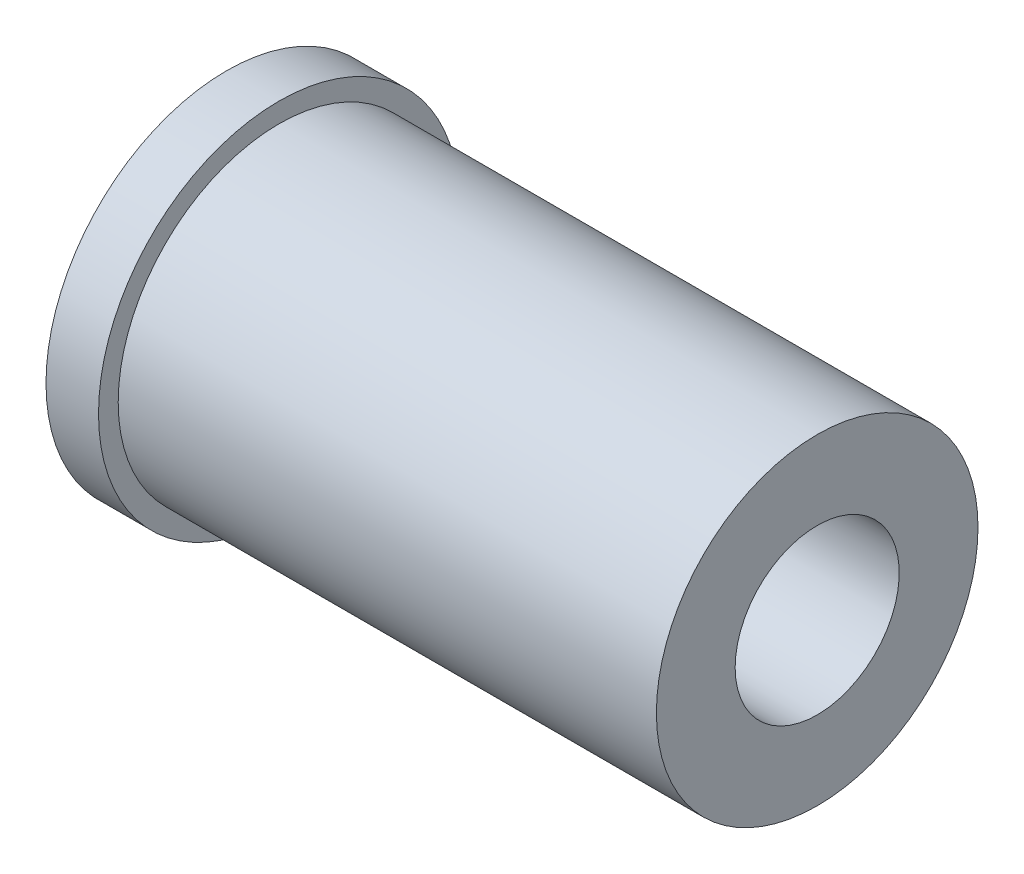
SolidWorks part; units mm, degrees
material "AISI 304"
ref_plane "前视基准面" through (0, 0, 0) normal (0, 0, 1) x (1, 0, 0)
ref_plane "上视基准面" through (0, 0, 0) normal (0, 1, 0) x (1, 0, 0)
ref_plane "右视基准面" through (0, 0, 0) normal (1, 0, 0) x (0, 0, -1)
sketch "草图1" plane through (0, 0, 0) normal (0, 0, 1) x (1, 0, 0)
  line L0 (0, 0) -> (7, 0) construction
  line L1 (0, 1.5) -> (0, 2.75)
  line L2 (0, 2.75) -> (0.8, 2.75)
  line L3 (0.8, 2.75) -> (0.8, 2.45)
  line L4 (0.8, 2.45) -> (9, 2.45)
  line L5 (9, 2.45) -> (9, 0)
  line L6 (9, 0) -> (3.5, 0)
  line L7 (3.5, 0) -> (3.5, 1.5)
  line L8 (3.5, 1.5) -> (0, 1.5)
  dimension "D1" = 9
  dimension "D2" = 1.5
  dimension "D3" = 3.5
  dimension "D4" = 2.45
  dimension "D5" = 2.75
  dimension "D6" = 0.8
revolve "旋转1" add sketch "草图1" angle 360 about L0
hole_wizard "M3 螺纹孔1" positions "草图2" profile "草图3" tap size "M3" standard "GB" end condition through all
sketch "草图2" plane through (3.5, 0, 0) normal (-1, 0, 0) x (0, 0, 1)
  point P0 (0, 0)
sketch "草图3" plane through (3.5, 0, 0) normal (0, 1, 0) x (0, 0, 1)
  line L0 (0, 0) -> (0, 5.5)
  line L1 (0, 5.5) -> (1.25, 5.5)
  line L2 (1.25, 5.5) -> (1.25, 0)
  line L5 (1.25, 0) -> (0, 0)
  line L11 (0, -6.35) -> (0, 107.95) construction
  dimension "通孔螺纹孔钻头直径" = 2.5
  dimension "通孔螺纹孔钻头深度" = 5.5
cosmetic thread "孔螺蚊线1" parameters "D2"=3
